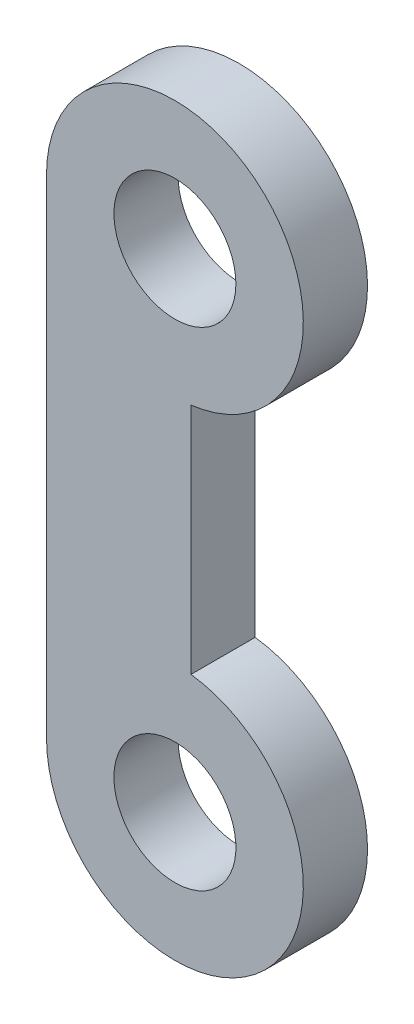
SolidWorks part; units mm, degrees
ref_plane "Płaszczyzna przednia" through (0, 0, 0) normal (0, 0, 1) x (1, 0, 0)
ref_plane "Płaszczyzna górna" through (0, 0, 0) normal (0, 1, 0) x (1, 0, 0)
ref_plane "Płaszczyzna prawa" through (0, 0, 0) normal (1, 0, 0) x (0, 0, -1)
sketch "Sketch1" plane through (0, 0, 0) normal (0, 0, 1) x (1, 0, 0)
  line L0 (-244.6939, 0) -> (11990.0031, 0) construction
  line L1 (-0.1262, 3.6327) -> (-0.1262, -3.6327)
  line L4 (-4.6262, 7.6014) -> (-4.6262, -7.6014)
  circle A0 centre (-0.6262, 7.6014) radius 1.9
  circle A1 centre (-0.6262, -7.6014) radius 1.9
  arc A2 (-0.1262, 3.6327) -> (-4.6262, 7.6014) centre (-0.6262, 7.6014) ccw
  arc A3 (-4.6262, -7.6014) -> (-0.1262, -3.6327) centre (-0.6262, -7.6014) ccw
  dimension "D1" = 3.8
  dimension "D2" = 4
  dimension "D3" = 0.5
extrude "Boss-Extrude1" add sketch "Sketch1" along normal blind 2
